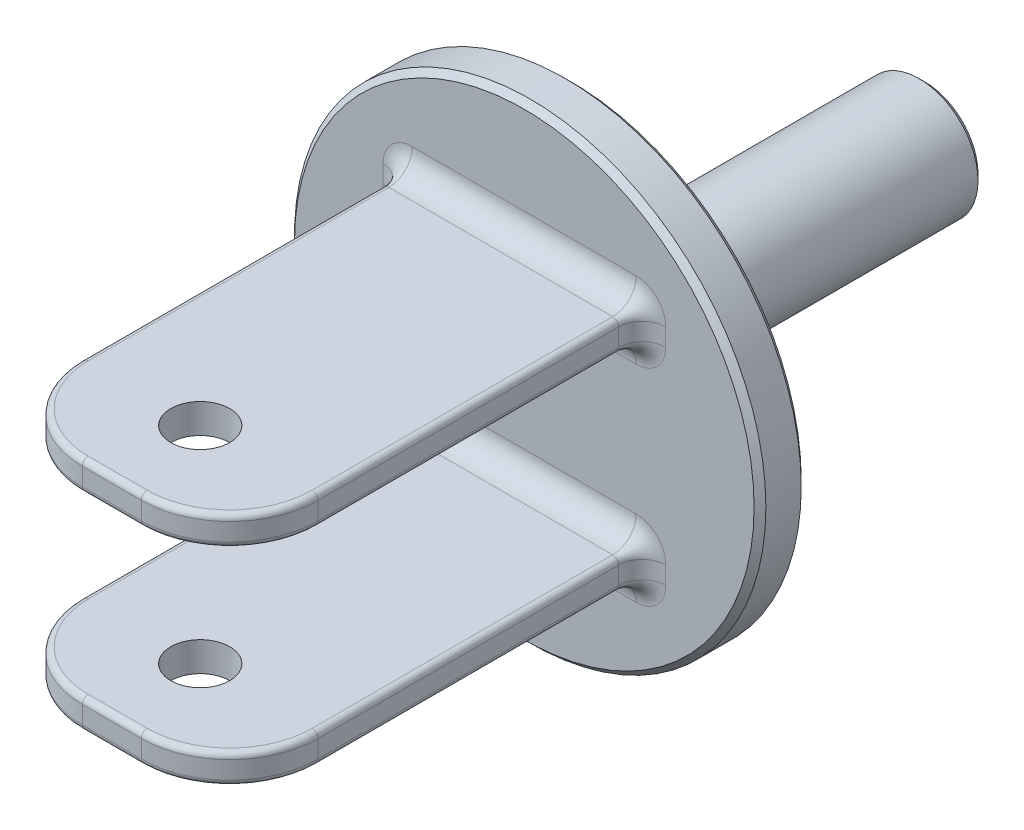
SolidWorks part; units mm, degrees
ref_plane "Front Plane" through (0, 0, 0) normal (0, 0, 1) x (1, 0, 0)
ref_plane "Top Plane" through (0, 0, 0) normal (0, 1, 0) x (1, 0, 0)
ref_plane "Right Plane" through (0, 0, 0) normal (1, 0, 0) x (0, 0, -1)
sketch "Sketch1" plane through (0, 0, 0) normal (0, 0, 1) x (1, 0, 0)
  circle A0 centre (0, 0) radius 40
  dimension "D2" = 80
extrude "Boss-Extrude1" add sketch "Sketch1" along normal blind 8
sketch "Sketch2" plane through (0, 0, 8) normal (0, 0, 1) x (1, 0, 0)
  line L0 (0, 0) -> (0, 17.5) construction
  line L1 (20, 20) -> (-20, 20)
  line L2 (20, 20) -> (20, 15)
  line L3 (20, 15) -> (-20, 15)
  line L4 (-20, 20) -> (-20, 15)
  line L5 (20, 20) -> (-20, 15) construction
  line L6 (20, 15) -> (-20, 20) construction
  point P0 (0, 17.5)
  dimension "D1" = 40
  dimension "D2" = 5
  dimension "D3" = 15
extrude "Boss-Extrude2" add sketch "Sketch2" along normal blind 70
fillet "Fillet1" radius 15 2 edges at (20, 17.5, 78) (-20, 17.5, 78)
fillet "Fillet2" radius 1 10 edges at (20, 20, 35.5) (15.6066, 20, 73.6066) (0, 20, 78) (-15.6066, 20, 73.6066) (20, 15, 35.5) (15.6066, 15, 73.6066) (0, 15, 78) (-15.6066, 15, 73.6066) (-20, 20, 35.5) (-20, 15, 35.5)
fillet "Fillet3" radius 4 8 edges at (-19.7071, 19.7071, 8) (0, 20, 8) (19.7071, 19.7071, 8) (20, 17.5, 8) (19.7071, 15.2929, 8) (0, 15, 8) (-19.7071, 15.2929, 8) (-20, 17.5, 8)
mirror "Mirror1" about plane through (0, 0, 0) normal (0, 1, 0) of "Fillet3", "Fillet2", "Boss-Extrude2", "Fillet1"
sketch "Sketch3" plane through (0, 20, 0) normal (0, 1, 0) x (1, 0, 0)
  line L0 (5, -78) -> (-5, -78) construction
  circle A0 centre (0, -63) radius 5
  point P2 (0, -78)
  dimension "D1" = 10
  dimension "D2" = 15
extrude "Cut-Extrude1" cut sketch "Sketch3" against normal through all
sketch "Sketch4" plane through (0, 0, 0) normal (0, 0, -1) x (-1, 0, 0)
  circle A0 centre (0, 0) radius 10
  circle A1 centre (0, 0) radius 7.5
  dimension "D1" = 20
  dimension "D2" = 15
extrude "Boss-Extrude3" add sketch "Sketch4" along normal blind 60
chamfer "Chamfer1" distance 1 angle 45 1 edges at (-10, 0, -60)
chamfer "Chamfer2" distance 1 angle 45 2 edges at (40, 0, 8) (40, 0, 0)
